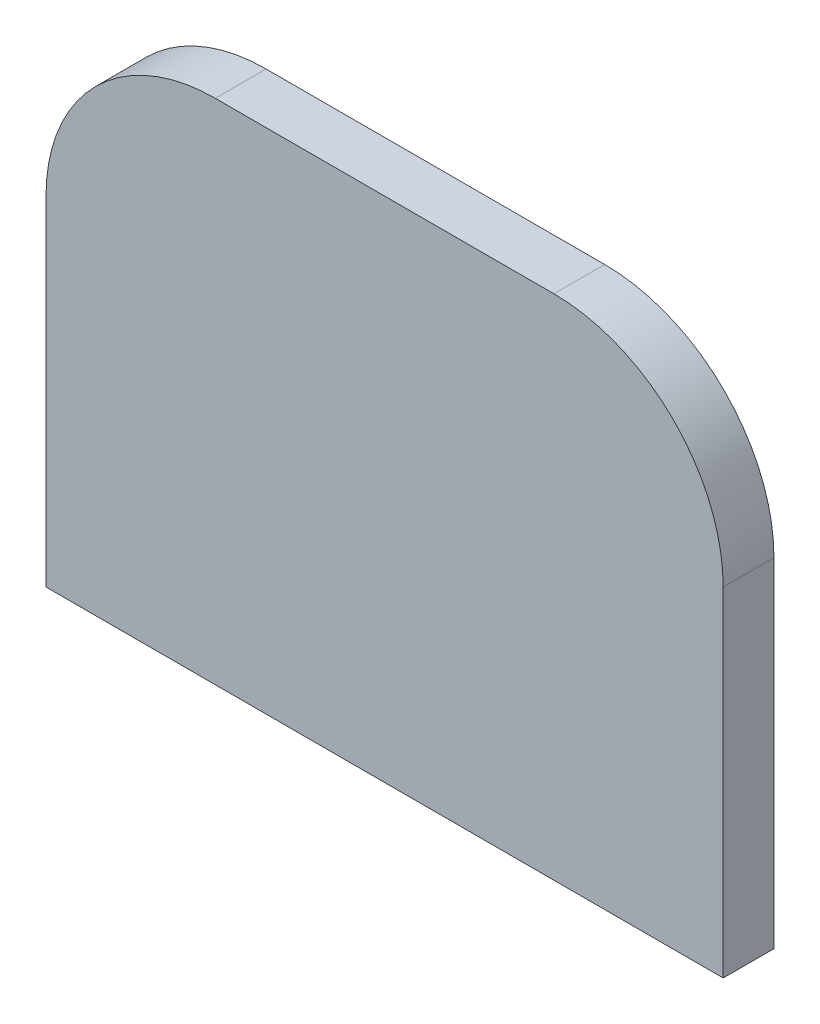
SolidWorks part; units mm, degrees
ref_plane "Front Plane" through (0, 0, 0) normal (0, 0, 1) x (1, 0, 0)
ref_plane "Top Plane" through (0, 0, 0) normal (0, 1, 0) x (1, 0, 0)
ref_plane "Right Plane" through (0, 0, 0) normal (1, 0, 0) x (0, 0, -1)
sketch "Sketch1" plane through (0, 0, 0) normal (0, 0, 1) x (1, 0, 0)
  line L1 (-20, 15) -> (20, 15)
  line L2 (-20, 15) -> (-20, -15)
  line L3 (-20, -15) -> (20, -15)
  line L4 (20, 15) -> (20, -15)
  line L5 (-20, 15) -> (20, -15) construction
  line L6 (-20, -15) -> (20, 15) construction
  point P0 (0, 0)
  dimension "D1" = 40
  dimension "D2" = 30
extrude "Boss-Extrude1" add sketch "Sketch1" along normal blind 3 separate body
fillet "Fillet1" radius 10 2 edges at (20, 15, 1.5) (-20, 15, 1.5)
